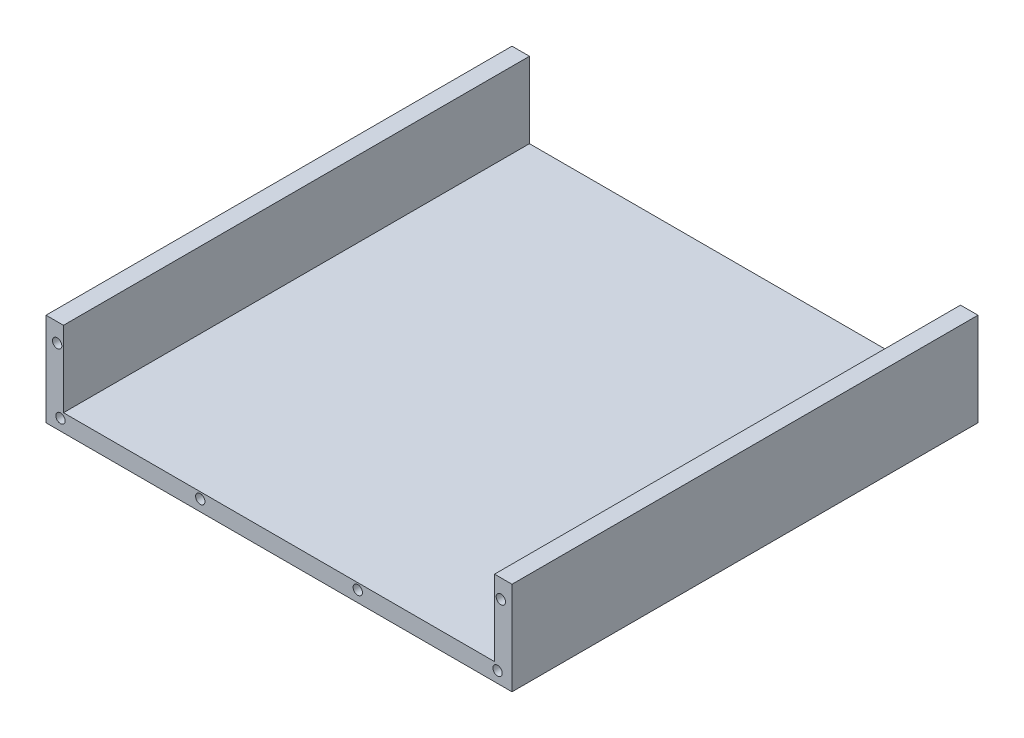
SolidWorks part; units mm, degrees
ref_plane "Front" through (0, 0, 0) normal (0, 0, 1) x (1, 0, 0)
ref_plane "Top" through (0, 0, 0) normal (0, 1, 0) x (1, 0, 0)
ref_plane "Right" through (0, 0, 0) normal (1, 0, 0) x (0, 0, -1)
sketch "Sketch1" plane through (0, 0, 0) normal (0, 0, 1) x (1, 0, 0)
  line L0 (0, -12.7) -> (0, 12.7) construction
  line L1 (-63.5, 0) -> (63.5, 0) construction
  line L2 (58.7375, 12.7) -> (-58.7375, 12.7) construction
  line L3 (-63.5, -12.7) -> (63.5, -12.7)
  line L4 (-63.5, -12.7) -> (-63.5, 12.7)
  line L5 (-63.5, 12.7) -> (63.5, 12.7)
  line L6 (63.5, -12.7) -> (63.5, 12.7)
  line L7 (-63.5, -12.7) -> (63.5, 12.7) construction
  line L8 (-63.5, 12.7) -> (63.5, -12.7) construction
  line L9 (-58.7375, -12.7) -> (58.7375, -12.7)
  point P3 (0, 0)
  point P4 (0, 0)
  point P8 (0, 0)
  point P13 (63.5, -7.9375)
  point P17 (0, 12.7)
  point P20 (0, -12.7)
  dimension "Outside Width" = 127
  dimension "Outside Height" = 25.4
  dimension "Inside Height" = 20.6375
  dimension "Wall Thickness" = 4.7625
  dimension "Inside Width" = 117.475
sketch "Sketch2" plane through (0, 0, 0) normal (1, 0, 0) x (0, 0, -1)
  line L0 (-63.5, 0) -> (63.5, 0) construction
  dimension "Length" = 127
sketch "Sketch3" plane through (0, 0, 0) normal (0, 0, 1) x (1, 0, 0)
  line L0 (-63.5, 12.7) -> (-63.5, -12.7)
  line L1 (-63.5, -12.7) -> (63.5, -12.7)
  line L2 (63.5, -12.7) -> (63.5, 12.7)
  line L3 (63.5, 12.7) -> (58.7375, 12.7)
  line L4 (58.7375, 12.7) -> (58.7375, -7.9375)
  line L5 (58.7375, -7.9375) -> (-58.7375, -7.9375)
  line L6 (-58.7375, -7.9375) -> (-58.7375, 12.7)
  line L7 (-58.7375, 12.7) -> (-63.5, 12.7)
  line L8 (-58.7375, -7.9375) -> (-58.7375, -12.7) construction
  dimension "D1" = 25.4
  dimension "D2" = 127
  dimension "D3" = 4.7625
extrude "Boss-Extrude2" add sketch "Sketch3" along normal mid plane 127
sketch "Reference Sketch1" plane through (0, 0, 0) normal (1, 0, 0) x (0, 0, -1)
  line L0 (-63.5, 0) -> (63.5, 0) construction
  point P0 (-19.05, 0)
  point P1 (19.05, 0)
  dimension "D1" = 44.45
  dimension "D2" = 44.45
sketch "Sketch4" plane through (0, 0, 63.5) normal (0, 0, 1) x (1, 0, 0)
  line L1 (-63.5, 12.7) -> (-63.5, -12.7) construction
  line L2 (-63.5, -12.7) -> (63.5, -12.7) construction
  line L3 (0, -13.97) -> (0, 13.97) construction
  line L4 (63.5, -12.7) -> (63.5, 12.7) construction
  line L5 (-58.7375, 12.7) -> (-63.5, 12.7) construction
  circle A0 centre (-60.452, 7.62) radius 1.27
  circle A2 centre (59.563, -9.652) radius 1.27
  circle A3 centre (60.452, 7.62) radius 1.27
  circle A4 centre (-21.463, -9.652) radius 1.27
  circle A5 centre (21.463, -9.652) radius 1.27
  circle A7 centre (-59.563, -9.652) radius 1.27
  dimension "D1" = 38.1
  dimension "D3" = 3.048
  dimension "D6" = 5.08
  dimension "D2" = 3.937
  dimension "D8" = 38.1
  dimension "D4" = 3.937
  dimension "D5" = 3.048
  dimension "D7" = 3.048
extrude "Cut-Extrude1" cut sketch "Sketch4" against normal blind 2.54 contours A5 | A3
sketch "Sketch5" plane through (0, 0, -63.5) normal (0, 0, -1) x (-1, 0, 0)
  line L0 (-63.5, 12.7) -> (-58.7375, 12.7) construction
  line L5 (-63.5, -12.7) -> (-63.5, 12.7) construction
  line L6 (63.5, -12.7) -> (-63.5, -12.7) construction
  line L7 (0, 13.97) -> (0, -13.97) construction
  circle A0 centre (-59.563, -9.652) radius 1.27
  circle A1 centre (-60.452, 7.62) radius 1.27
  circle A2 centre (-21.463, -9.652) radius 1.27
  circle A6 centre (21.463, -9.652) radius 1.27
  circle A7 centre (60.452, 7.62) radius 1.27
  circle A8 centre (59.563, -9.652) radius 1.27
  dimension "D1" = 3.048
  dimension "D3" = 3.937
  dimension "D2" = 5.08
  dimension "D4" = 3.048
  dimension "D5" = 38.1
extrude "Cut-Extrude2" cut sketch "Sketch5" against normal blind 2.54
equation "\"D1@Sketch3\" = \"Outside Height@Sketch1\""
equation "\"D2@Sketch3\" = \"Outside Width@Sketch1\""
equation "\"D3@Sketch3\" = \"Wall Thickness@Sketch1\""
equation "\"D2@Reference Sketch1\" = \"D1@Reference Sketch1\""
equation "\"D1@Boss-Extrude2\" = \"Length@Sketch2\""
equation "\"Inside Height@Sketch1\"=\"Outside Height@Sketch1\"-\"Wall Thickness@Sketch1\""
equation "\"Inside Width@Sketch1\"=\"Outside Width@Sketch1\"-\"Wall Thickness@Sketch1\"*2"
